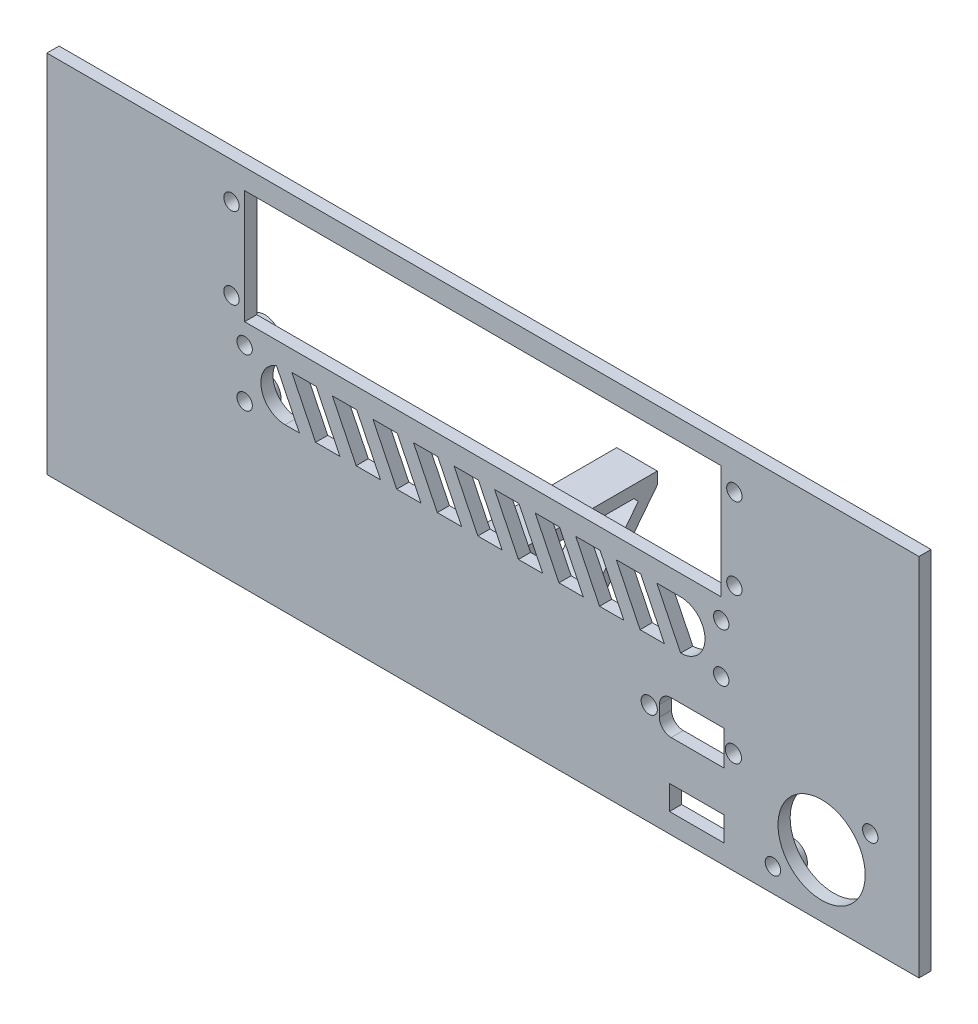
SolidWorks part; units mm, degrees
ref_plane "Płaszczyzna przednia" through (0, 0, 0) normal (0, 0, 1) x (1, 0, 0)
ref_plane "Płaszczyzna górna" through (0, 0, 0) normal (0, 1, 0) x (1, 0, 0)
ref_plane "Płaszczyzna prawa" through (0, 0, 0) normal (1, 0, 0) x (0, 0, -1)
sketch "Szkic1" plane through (0, 0, 0) normal (0, 0, 1) x (1, 0, 0)
  line L1 (0, 0) -> (215, 0)
  line L2 (0, 0) -> (0, 90)
  line L3 (0, 90) -> (215, 90)
  line L4 (215, 0) -> (215, 90)
  dimension "D1" = 215
  dimension "D2" = 90
extrude "Dodanie-wyciągnięcie1" add sketch "Szkic1" along normal blind 3
ref_plane "Płaszczyzna1" through (107.5, 0, 0) normal (1, 0, 0) x (0, 0, -1)
sketch "Szkic3" plane through (107.5, 0, 0) normal (1, 0, 0) x (0, 0, -1)
  line L0 (0, 3) -> (10, 3)
  line L1 (0, 38) -> (35, 38)
  line L2 (0, 0) -> (0, 90) construction
  line L3 (3, 11.5415) -> (3, 35)
  line L4 (3, 35) -> (31.193, 35)
  line L5 (35, 35) -> (35, 38)
  line L6 (0, 38) -> (0, 3)
  line L7 (9.7992, 7.6159) -> (3, 11.5415)
  line L8 (35, 35) -> (10, 3)
  line L9 (31.193, 35) -> (9.7992, 7.6159)
  dimension "D1" = 10
  dimension "D2" = 3
  dimension "D3" = 35
  dimension "D4" = 35
  dimension "D5" = 3
  dimension "D6" = 3
  dimension "D7" = 97.999
  dimension "D8" = 28.193
  dimension "D9" = 3
extrude "Dodanie-wyciągnięcie3" add sketch "Szkic3" along normal mid plane 10
sketch "Szkic4" plane through (0, 3, 0) normal (0, -1, 0) x (1, 0, 0)
  line L0 (102.5, 0) -> (102.5, -10) construction
  line L2 (112.5, -10) -> (102.5, -10) construction
  circle A0 centre (107.5, -5) radius 1.9
  point P6 (107.4554, -10)
  dimension "D3" = 3.8
  dimension "D1" = 5
  dimension "D2" = 5
extrude "Wytnij-wyciągnięcie1" cut sketch "Szkic4" against normal blind 10
sketch "Szkic5" plane through (0, 0, 3) normal (0, 0, 1) x (1, 0, 0)
  line L0 (215, 90) -> (0, 90) construction
  line L1 (48.75, 85) -> (166.25, 85)
  line L2 (48.75, 85) -> (48.75, 57)
  line L3 (48.75, 57) -> (166.25, 57)
  line L4 (166.25, 85) -> (166.25, 57)
  line L5 (107.5, 90) -> (107.5, 105.9064) construction
  line L6 (48.75, 71) -> (107.5, 71) construction
  circle A0 centre (45.5, 81) radius 1.9
  circle A2 centre (45.5, 61) radius 1.9
  circle A3 centre (169.5, 61) radius 1.9
  circle A4 centre (169.5, 81) radius 1.9
  point P6 (107.5, 85)
  point P19 (0, 0)
  dimension "D6" = 3.8
  dimension "D4" = 20
  dimension "D1" = 5
  dimension "D2" = 28
  dimension "D3" = 117.5
  dimension "D5" = 62
extrude "Wytnij-wyciągnięcie2" cut sketch "Szkic5" against normal blind 35 contours A0 | A2 | A3 | A4 | L2 L3 L4 L1
chamfer "Sfazowanie1" distance 2 angle 45 3 edges at (107.5, 7.6159, -9.7992) (107.5, 35, -31.193) (107.5, 35, -3)
sketch "Szkic6" plane through (0, 0, 3) normal (0, 0, 1) x (1, 0, 0)
  line L1 (153.5, 10.8) -> (167, 10.8)
  line L2 (153.5, 10.8) -> (153.5, 4.8)
  line L3 (153.5, 4.8) -> (167, 4.8)
  line L4 (167, 10.8) -> (167, 4.8)
  line L10 (215, 0) -> (215, 90) construction
  line L11 (0, 0) -> (215, 0) construction
  line L13 (167, 20.8) -> (153.9, 20.8)
  line L14 (167, 20.8) -> (167, 29.3)
  line L15 (167, 29.3) -> (153.9, 29.3)
  line L16 (151, 23.7) -> (151, 26.4)
  circle A0 centre (191, 15.35) radius 10.75
  circle A1 centre (203, 24.85) radius 1.9
  circle A2 centre (179, 5.85) radius 1.9
  arc A3 (153.9, 20.8) -> (151, 23.7) centre (153.9, 23.7) cw
  arc A4 (153.9, 29.3) -> (151, 26.4) centre (153.9, 26.4) ccw
  circle A5 centre (148.5, 25.05) radius 2
  circle A6 centre (169.25, 25.05) radius 2
  point P16 (151, 20.8)
  dimension "D9" = 3.8
  dimension "D10" = 3.8
  dimension "D15" = 21.5
  dimension "D16" = 2.9
  dimension "D21" = 4
  dimension "D22" = 4
  dimension "D3" = 8.5
  dimension "D4" = 16
  dimension "D1" = 48
  dimension "D2" = 13.5
  dimension "D5" = 6
  dimension "D6" = 4.8
  dimension "D7" = 24
  dimension "D8" = 15.35
  dimension "D11" = 12
  dimension "D12" = 9.5
  dimension "D13" = 12
  dimension "D14" = 9.5
  dimension "D17" = 24
  dimension "D18" = 10
  dimension "D19" = 2.5
  dimension "D20" = 2.25
extrude "Wytnij-wyciągnięcie3" cut sketch "Szkic6" against normal through all
sketch "Szkic8" plane through (0, 0, 0) normal (0, 0, -1) x (-1, 0, 0)
  circle A0 centre (-179, 5.85) radius 3.5
  circle A1 centre (-203, 24.85) radius 3.5
  circle A2 centre (-203, 24.85) radius 2
  circle A3 centre (-179, 5.85) radius 2
  dimension "D1" = 7
  dimension "D2" = 7
  dimension "D3" = 4
  dimension "D4" = 4
extrude "Dodanie-wyciągnięcie4" add sketch "Szkic8" along normal blind 2
sketch "Szkic9" plane through (0, 0, 0) normal (0, 0, -1) x (-1, 0, 0)
  line L0 (-156.25, 46) -> (-58.75, 46) construction
  line L1 (-156.25, 52) -> (-58.75, 52)
  line L2 (-156.25, 40) -> (-58.75, 40)
  line L3 (-166.25, 57) -> (-48.75, 57) construction
  line L4 (-166.25, 57) -> (-166.25, 85) construction
  line L5 (-48.75, 57) -> (-48.75, 85) construction
  line L6 (-156.25, 40) -> (-150.385, 52)
  line L7 (-152.25, 40) -> (-146.385, 52)
  line L8 (-146.25, 40) -> (-140.385, 52)
  line L9 (-142.25, 40) -> (-136.385, 52)
  line L10 (-136.25, 40) -> (-130.385, 52)
  line L11 (-132.25, 40) -> (-126.385, 52)
  line L12 (-126.25, 40) -> (-120.385, 52)
  line L13 (-122.25, 40) -> (-116.385, 52)
  line L14 (-116.25, 40) -> (-110.385, 52)
  line L15 (-112.25, 40) -> (-106.385, 52)
  line L16 (-106.25, 40) -> (-100.385, 52)
  line L17 (-102.25, 40) -> (-96.385, 52)
  line L18 (-96.25, 40) -> (-90.385, 52)
  line L19 (-92.25, 40) -> (-86.385, 52)
  line L20 (-86.25, 40) -> (-80.385, 52)
  line L21 (-82.25, 40) -> (-76.385, 52)
  line L22 (-76.25, 40) -> (-70.385, 52)
  line L23 (-72.25, 40) -> (-66.385, 52)
  line L24 (-66.25, 40) -> (-60.385, 52)
  line L25 (-62.25, 40) -> (-56.583, 51.595)
  line L26 (-107.5, 38) -> (-107.5, 71.4956) construction
  line L28 (-112.5, 38) -> (-102.5, 38) construction
  line L29 (-107.5, 46) -> (-179.9248, 46) construction
  arc A0 (-156.25, 52) -> (-156.25, 40) centre (-156.25, 46) ccw
  arc A1 (-58.75, 40) -> (-58.75, 52) centre (-58.75, 46) ccw
  circle A2 centre (-166.25, 52) radius 1.9
  circle A3 centre (-166.25, 40) radius 1.9
  circle A4 centre (-48.75, 40) radius 1.9
  circle A5 centre (-48.75, 52) radius 1.9
  point P2 (-107.5, 46)
  point P61 (0, 0)
  dimension "D7" = 3.8
  dimension "D1" = 11
  dimension "D2" = 10
  dimension "D3" = 10
  dimension "D4" = 12
  dimension "D5" = 4
  dimension "D8" = 6
  dimension "D9" = 10
  dimension "D6" = 10
extrude "Wytnij-wyciągnięcie4" cut sketch "Szkic9" against normal blind 3 contours A2 | A3 | L1 A0 L6 | L2 L8 L1 L7 | L2 L10 L1 L9 | L2 L12 L1 L11 | L2 L14 L1 L13 | L2 L16 L1 L15 | L2 L18 L1 L17 | L2 L20 L1 L19 | L2 L22 L1 L21 | L2 L24 L1 L23 | L2 A1 L25 | A4 | A5
sketch "Szkic10" plane through (0, 0, 0) normal (0, 0, -1) x (-1, 0, 0)
  circle A0 centre (-166.25, 40) radius 1.9
  circle A2 centre (-166.25, 52) radius 1.9
  circle A3 centre (-48.75, 52) radius 1.9
  circle A4 centre (-48.75, 40) radius 1.9
  circle A5 centre (-166.25, 52) radius 4
  circle A6 centre (-166.25, 40) radius 4
  circle A7 centre (-48.75, 40) radius 4
  circle A8 centre (-48.75, 52) radius 4
  dimension "D1" = 8
extrude "Dodanie-wyciągnięcie5" add sketch "Szkic10" along normal blind 2
